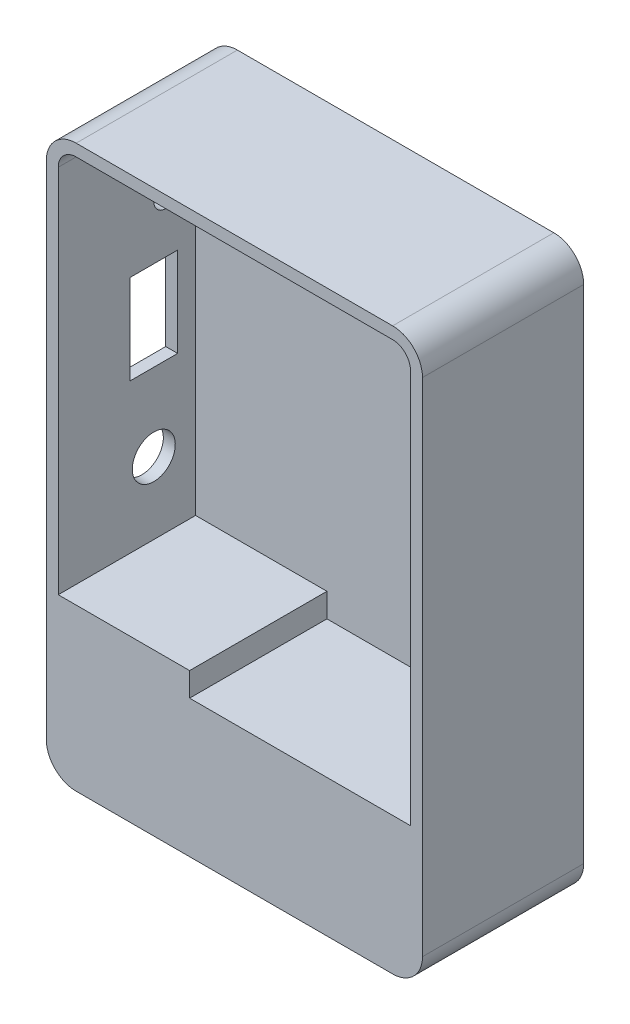
SolidWorks part; units mm, degrees
ref_plane "Plan de face" through (0, 0, 0) normal (0, 0, 1) x (1, 0, 0)
ref_plane "Plan de dessus" through (0, 0, 0) normal (0, 1, 0) x (1, 0, 0)
ref_plane "Plan de droite" through (0, 0, 0) normal (1, 0, 0) x (0, 0, -1)
sketch "Esquisse1" plane through (0, 0, 0) normal (0, 0, 1) x (1, 0, 0)
  line L1 (5, 0) -> (58, 0)
  line L2 (0, 5) -> (0, 89)
  line L3 (5, 94) -> (58, 94)
  line L4 (63, 5) -> (63, 89)
  arc A0 (0, 5) -> (5, 0) centre (5, 5) ccw
  arc A1 (63, 5) -> (58, 0) centre (58, 5) cw
  arc A2 (63, 89) -> (58, 94) centre (58, 89) ccw
  arc A3 (5, 94) -> (0, 89) centre (5, 89) ccw
  point P7 (0, 0)
  point P10 (63, 0)
  point P13 (63, 94)
  point P16 (0, 94)
  dimension "D3" = 5
  dimension "D1" = 63
  dimension "D2" = 94
extrude "Boss.-Extru.1" add sketch "Esquisse1" along normal blind 27
sketch "Esquisse2" plane through (0, 0, 0) normal (-1, 0, 0) x (0, 0, 1)
  line L0 (9, 84) -> (9, 76) construction
  line L1 (11, 84) -> (11, 76)
  line L2 (7, 84) -> (7, 76)
  line L3 (0, 89) -> (0, 5) construction
  line L5 (27, 89) -> (0, 89) construction
  line L7 (7, 67) -> (15, 67)
  line L8 (7, 67) -> (7, 52)
  line L9 (7, 52) -> (15, 52)
  line L10 (15, 67) -> (15, 52)
  arc A0 (11, 84) -> (7, 84) centre (9, 84) ccw
  arc A1 (7, 76) -> (11, 76) centre (9, 76) ccw
  circle A2 centre (11, 39) radius 3.6
  point P2 (9, 80)
  dimension "D1" = 9
  dimension "D7" = 13
  dimension "D2" = 5
  dimension "D3" = 8
  dimension "D4" = 22
  dimension "D5" = 8
  dimension "D6" = 15
extrude "Enlèv. mat.-Extru.1" cut sketch "Esquisse2" against normal blind 9
sketch "Esquisse3" plane through (0, 0, 0) normal (0, -1, 0) x (1, 0, 0)
  line L0 (5, 27) -> (5, 0) construction
  line L1 (5, 8) -> (21, 8)
  line L2 (5, 8) -> (5, 22)
  line L3 (5, 22) -> (21, 22)
  line L4 (21, 8) -> (21, 22)
  line L5 (5, 0) -> (58, 0) construction
  line L7 (24, 8) -> (39, 8)
  line L8 (24, 8) -> (24, 24)
  line L9 (24, 24) -> (39, 24)
  line L10 (39, 8) -> (39, 24)
  line L11 (42, 8) -> (57, 8)
  line L12 (42, 8) -> (42, 24)
  line L13 (42, 24) -> (57, 24)
  line L14 (57, 8) -> (57, 24)
  dimension "D1" = 16
  dimension "D2" = 14
  dimension "D3" = 8
  dimension "D4" = 3
  dimension "D5" = 15
  dimension "D6" = 16
  dimension "D7" = 3
  dimension "D8" = 16
  dimension "D9" = 15
extrude "Enlèv. mat.-Extru.2" cut sketch "Esquisse3" against normal blind 19
sketch "Esquisse4" plane through (0, 0, 27) normal (0, 0, 1) x (1, 0, 0)
  line L0 (58, 94) -> (5, 94) construction
  line L1 (2, 27) -> (24, 27)
  line L2 (2, 27) -> (2, 89)
  line L3 (5, 92) -> (58, 92)
  line L4 (61, 27) -> (61, 89)
  line L5 (0, 89) -> (0, 5) construction
  line L6 (63, 5) -> (63, 89) construction
  line L9 (61, 27) -> (61, 23)
  line L10 (61, 23) -> (24, 23)
  line L11 (24, 27) -> (24, 23)
  arc A0 (5, 92) -> (2, 89) centre (5, 89) ccw
  arc A1 (58, 92) -> (61, 89) centre (58, 89) cw
  dimension "D4" = 3
  dimension "D5" = 3
  dimension "D1" = 2
  dimension "D2" = 2
  dimension "D3" = 2
  dimension "D6" = 65
  dimension "D7" = 4
  dimension "D8" = 37
extrude "Enlèv. mat.-Extru.3" cut sketch "Esquisse4" against normal blind 23
